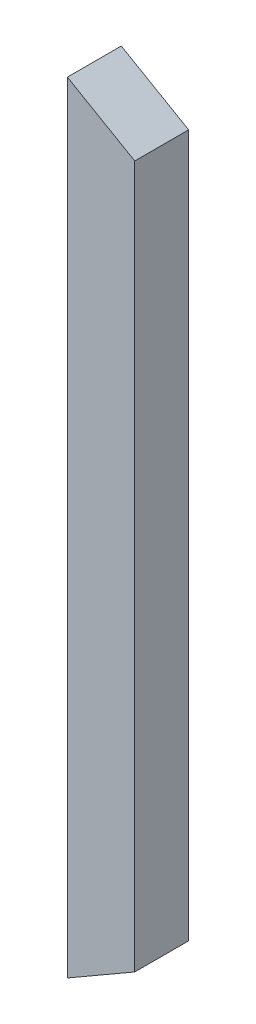
SolidWorks part; units mm, degrees
ref_plane "Plan de face" through (0, 0, 0) normal (0, 0, 1) x (1, 0, 0)
ref_plane "Plan de dessus" through (0, 0, 0) normal (0, 1, 0) x (1, 0, 0)
ref_plane "Plan de droite" through (0, 0, 0) normal (1, 0, 0) x (0, 0, -1)
sketch "Esquisse1" plane through (0, 0, 0) normal (0, 0, 1) x (1, 0, 0)
  line L1 (0, 0) -> (50, 0)
  line L2 (0, 0) -> (0, 550)
  line L3 (0, 550) -> (50, 550)
  line L4 (50, 0) -> (50, 550)
  dimension "D1" = 550
  dimension "D2" = 50
extrude "Boss.-Extru.1" add sketch "Esquisse1" along normal blind 40
sketch "Esquisse2" plane through (0, 0, 40) normal (0, 0, 1) x (1, 0, 0)
  line L0 (50, 0) -> (0, 0)
  line L1 (0, 0) -> (0, -28.8675)
  line L2 (0, -28.8675) -> (50, 0)
  dimension "D1" = 30
extrude "Boss.-Extru.2" add sketch "Esquisse2" against normal up to vertex (40 mm away) up to point (50, 0, 0)
sketch "Esquisse3" plane through (0, 0, 40) normal (0, 0, 1) x (1, 0, 0)
  line L0 (50, 521.1325) -> (0, 550)
  line L1 (50, 0) -> (50, 550) construction
  line L2 (0, 550) -> (50, 550)
  line L3 (50, 550) -> (50, 521.1325)
  dimension "D1" = 30
extrude "Enlèv. mat.-Extru.1" cut sketch "Esquisse3" against normal through all both and the other way through all
